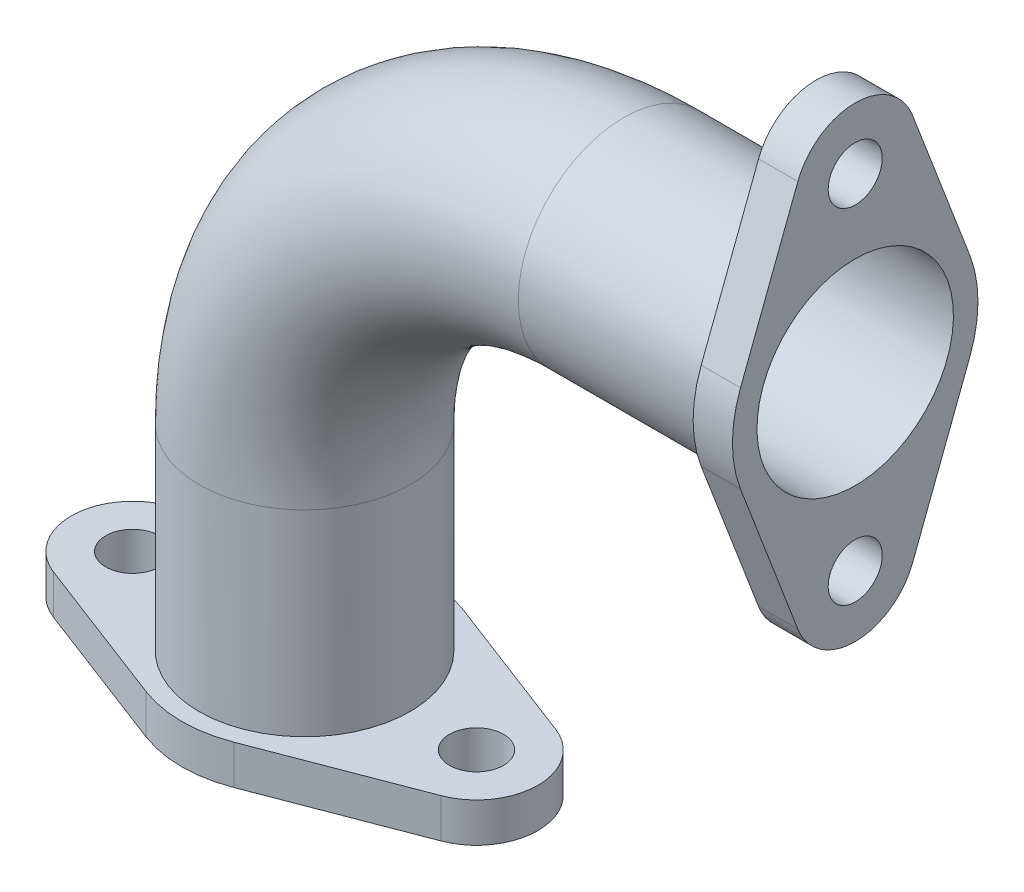
SolidWorks part; units mm, degrees
ref_plane "Front Plane" through (0, 0, 0) normal (0, 0, 1) x (1, 0, 0)
ref_plane "Top Plane" through (0, 0, 0) normal (0, 1, 0) x (1, 0, 0)
ref_plane "Right Plane" through (0, 0, 0) normal (1, 0, 0) x (0, 0, -1)
sketch "Sketch1" plane through (0, 0, 0) normal (0, 0, 1) x (1, 0, 0)
  line L1 (-43.5, 0) -> (-43.5, -40)
  line L2 (-86.5, 0) -> (-86.5, -40)
  line L3 (-86.5, -40) -> (-43.5, -40)
  line L4 (0, 43.5) -> (40, 43.5)
  line L5 (0, 86.5) -> (40, 86.5)
  line L6 (40, 86.5) -> (40, 43.5)
  line L7 (40, 65) -> (0, 65)
  line L8 (-65, 0) -> (-65, -40)
  arc A0 (0, 86.5) -> (-86.5, 0) centre (0, 0) ccw
  arc A1 (0, 43.5) -> (-43.5, 0) centre (0, 0) ccw
  arc A2 (0, 65) -> (-65, 0) centre (0, 0) ccw
  dimension "D1" = 86.5
  dimension "D2" = 43.5
  dimension "D3" = 40
  dimension "D4" = 40
sweep "Sweep4" add path "Sketch1" circular profile diameter 43 parameters "D3"=43
sketch "Sketch21" plane through (0, -40, 0) normal (0, -1, 0) x (1, 0, 0)
  line L0 (-112.5, 0) -> (-17.5, 0)
  line L1 (-65, -21.5) -> (-65, 21.5)
  line L2 (-104.4643, 11.6756) -> (-73.9286, 23.3512)
  line L3 (-104.4643, -11.6756) -> (-73.9286, -23.3512)
  line L4 (-25.5357, 11.6756) -> (-56.0714, 23.3512)
  line L5 (-25.5357, -11.6756) -> (-56.0714, -23.3512)
  circle A1 centre (-100, 0) radius 5.5
  circle A3 centre (-65, 0) radius 17.5
  arc A4 (-104.4643, -11.6756) -> (-104.4643, 11.6756) centre (-100, 0) cw
  arc A5 (-25.5357, -11.6756) -> (-25.5357, 11.6756) centre (-30, 0) ccw
  arc A6 (-73.9286, -23.3512) -> (-56.0714, -23.3512) centre (-65, 0) ccw
  circle A7 centre (-30, 0) radius 5.5
  arc A8 (-56.0714, 23.3512) -> (-73.9286, 23.3512) centre (-65, 0) ccw
  circle A9 centre (-65, 0) radius 21.5 construction
  point P10 (-65, 0)
  point P11 (-65, 0)
  circle M14 centre (-65, 0) radius 21.5
  dimension "D2" = 35
  dimension "D4" = 11
  dimension "D5" = 12.5
  dimension "D6" = 50
  dimension "D1" = 95
extrude "Boss-Extrude5" add sketch "Sketch21" along normal blind 8 contours L4 A8 L2 A4 L0 A1 A7 A5 M14 | L0 A7 A1 A4 L3 A6 L5 A5 M14 | A3 L1 L0 M14 | A3 L0 L1 M14 | A3 L1 L0 M14 | A3 L0 L1 M14
sketch "Sketch24" plane through (40, 0, 0) normal (1, 0, 0) x (0, 0, -1)
  line L0 (-0.8982, 18.5275) -> (-0.8982, 113.5275)
  line L1 (20.6018, 66.0275) -> (-22.3982, 66.0275)
  line L2 (-12.5738, 26.5632) -> (-24.2494, 57.0989)
  line L3 (10.7774, 26.5632) -> (22.4531, 57.0989)
  line L4 (-12.5738, 105.4918) -> (-24.2494, 74.9561)
  line L5 (10.7774, 105.4918) -> (22.4531, 74.9561)
  circle A0 centre (-0.8982, 31.0275) radius 5.5
  circle A1 centre (-0.8982, 66.0275) radius 17.5
  arc A2 (10.7774, 26.5632) -> (-12.5738, 26.5632) centre (-0.8982, 31.0275) cw
  arc A3 (10.7774, 105.4918) -> (-12.5738, 105.4918) centre (-0.8982, 101.0275) ccw
  arc A4 (22.4531, 57.0989) -> (22.4531, 74.9561) centre (-0.8982, 66.0275) ccw
  circle A5 centre (-0.8982, 101.0275) radius 5.5
  arc A6 (-24.2494, 74.9561) -> (-24.2494, 57.0989) centre (-0.8982, 66.0275) ccw
  circle A7 centre (0, 65) radius 21.5 construction
  point P6 (-0.8982, 66.0275)
  point P7 (-0.8982, 66.0275)
  dimension "D1" = 11
  dimension "D2" = 35
  dimension "D3" = 12.5
  dimension "D4" = 25
  dimension "D5" = 10.7774
  dimension "D6" = 20.6018
  dimension "D7" = 22.4531
  dimension "D8" = 1.0275
extrude "Boss-Extrude6" add sketch "Sketch24" along normal blind 8
sketch "Sketch26" plane through (0, -48, 0) normal (0, -1, 0) x (1, 0, 0)
  line L0 (-65, -25) -> (-65, 25)
  arc A0 (-73.9286, -23.3512) -> (-56.0714, -23.3512) centre (-65, 0) ccw construction
  arc A1 (-56.0714, 23.3512) -> (-73.9286, 23.3512) centre (-65, 0) ccw construction
  circle A2 centre (-65, 0) radius 20
  dimension "D1" = 40
extrude "Cut-Extrude1" cut sketch "Sketch26" against normal blind 48 contours A2
sketch "Sketch27" plane through (48, 0, 0) normal (1, 0, 0) x (0, 0, -1)
  line L0 (24.1018, 66.0275) -> (-25.8982, 66.0275)
  arc A0 (22.4531, 57.0989) -> (22.4531, 74.9561) centre (-0.8982, 66.0275) ccw construction
  arc A1 (-24.2494, 74.9561) -> (-24.2494, 57.0989) centre (-0.8982, 66.0275) ccw construction
  circle A2 centre (-0.8982, 66.0275) radius 20
  dimension "D1" = 40
extrude "Cut-Extrude2" cut sketch "Sketch27" against normal blind 48 contours A2
sketch "Sketch28" plane through (0, 0, 0) normal (0, 0, 1) x (1, 0, 0)
  line L0 (0, 86.5) -> (0, 43.5) construction
  line L1 (-85, 0) -> (-45, 0) construction
  arc A0 (0, 65) -> (-65, 0) centre (0, 0) ccw
  arc A1 (-85.0881, 0) -> (0, 85.0881) centre (0, 0) cw
  arc A2 (-45.2474, 0) -> (0, 45.2474) centre (0, 0) cw
sweep "Cut-Sweep1" cut path "Sketch28" circular profile diameter 40 parameters "D3"=40
